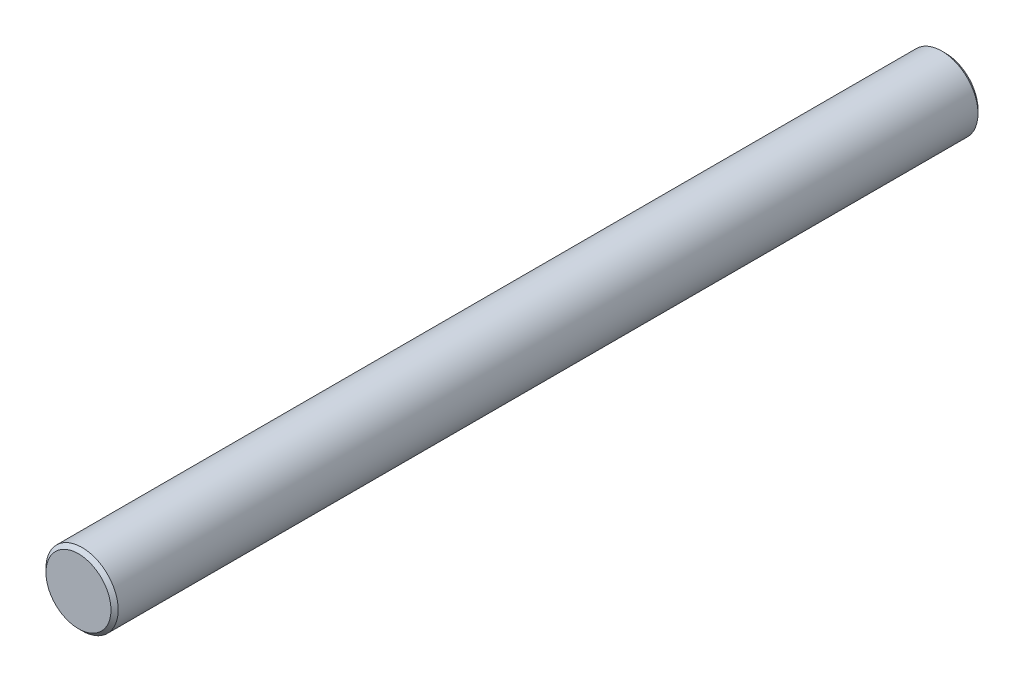
SolidWorks part; units mm, degrees
material "AISI 304"
ref_plane "Front Plane" through (0, 0, 0) normal (0, 0, 1) x (1, 0, 0)
ref_plane "Top Plane" through (0, 0, 0) normal (0, 1, 0) x (1, 0, 0)
ref_plane "Right Plane" through (0, 0, 0) normal (1, 0, 0) x (0, 0, -1)
sketch "Sketch1" plane through (0, 0, 0) normal (0, 0, 1) x (1, 0, 0)
  circle A0 centre (0, 0) radius 2.5
  dimension "D1" = 5
extrude "Boss-Extrude1" add sketch "Sketch1" along normal blind 60
chamfer "Chamfer1" distance 0.25 angle 45 2 edges at (2.5, 0, 0) (2.5, 0, 60)
